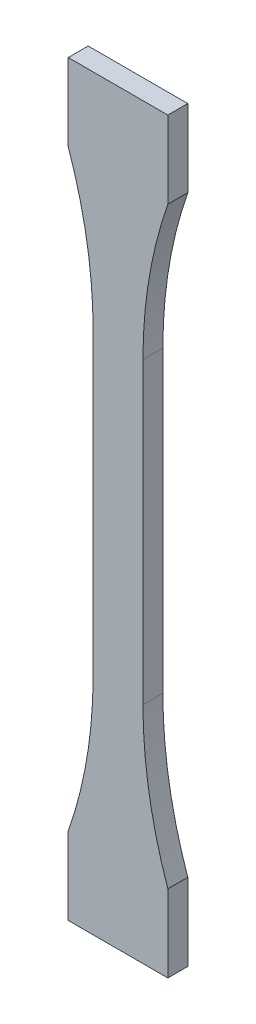
SolidWorks part; units mm, degrees
material "PET"
ref_plane "Plan de face" through (0, 0, 0) normal (0, 0, 1) x (1, 0, 0)
ref_plane "Plan de dessus" through (0, 0, 0) normal (0, 1, 0) x (1, 0, 0)
ref_plane "Plan de droite" through (0, 0, 0) normal (1, 0, 0) x (0, 0, -1)
sketch "Esquisse1" plane through (0, 0, 0) normal (0, 0, 1) x (1, 0, 0)
  line L0 (0, 75) -> (0, 0) construction
  line L1 (-10, 75) -> (10, 75)
  line L2 (-10, 75) -> (-10, 59.5)
  line L3 (-10, -75) -> (10, -75)
  line L4 (10, 75) -> (10, 59.5)
  line L5 (0, 30) -> (0, 0) construction
  line L6 (0, 0) -> (5, 0) construction
  line L7 (-5, 30) -> (5, 30)
  line L8 (-5, 30) -> (-5, -30)
  line L9 (-5, -30) -> (5, -30)
  line L10 (5, 30) -> (5, -30)
  line L11 (0, 0) -> (5, 0) construction
  line L12 (-10, 59.5) -> (10, 59.5) construction
  line L13 (-10, -59.5) -> (10, -59.5) construction
  line L14 (-10, -59.5) -> (-10, -75)
  line L15 (10, -59.5) -> (10, -75)
  line L16 (-10, 59.5) -> (-10, -59.5) construction
  line L17 (10, 59.5) -> (10, -59.5) construction
  line L18 (-5, 30) -> (-94.525, 30) construction
  line L19 (-5, -30) -> (-94.525, -30) construction
  arc A0 (-5, 30) -> (-10, 59.5) centre (-94.525, 30) ccw
  arc A1 (5, 30) -> (10, 59.5) centre (94.525, 30) cw
  arc A2 (-10, -59.5) -> (-5, -30) centre (-94.525, -30) ccw
  arc A3 (10, -59.5) -> (5, -30) centre (94.525, -30) cw
  dimension "D11" = 89.525
  dimension "D6" = 89.525
  dimension "L3" = 150
  dimension "B2" = 20
  dimension "B1" = 10
  dimension "L1" = 60
  dimension "L2" = 119
extrude "Boss.-Extru.1" add sketch "Esquisse1" along normal blind 4 contours L7 A1 L4 L1 L2 A0 | L10 L7 L8 L9 | L15 A3 L9 A2 L14 L3
equation "\"D6@Esquisse1\"=((\"L2@Esquisse1\"-\"L1@Esquisse1\")^2+(\"B2@Esquisse1\"-\"B1@Esquisse1\")^2)/(4*(\"B2@Esquisse1\"-\"B1@Esquisse1\"))"
equation "\"D11@Esquisse1\"=((\"L2@Esquisse1\"-\"L1@Esquisse1\")^2+(\"B2@Esquisse1\"-\"B1@Esquisse1\")^2)/(4*(\"B2@Esquisse1\"-\"B1@Esquisse1\"))"
